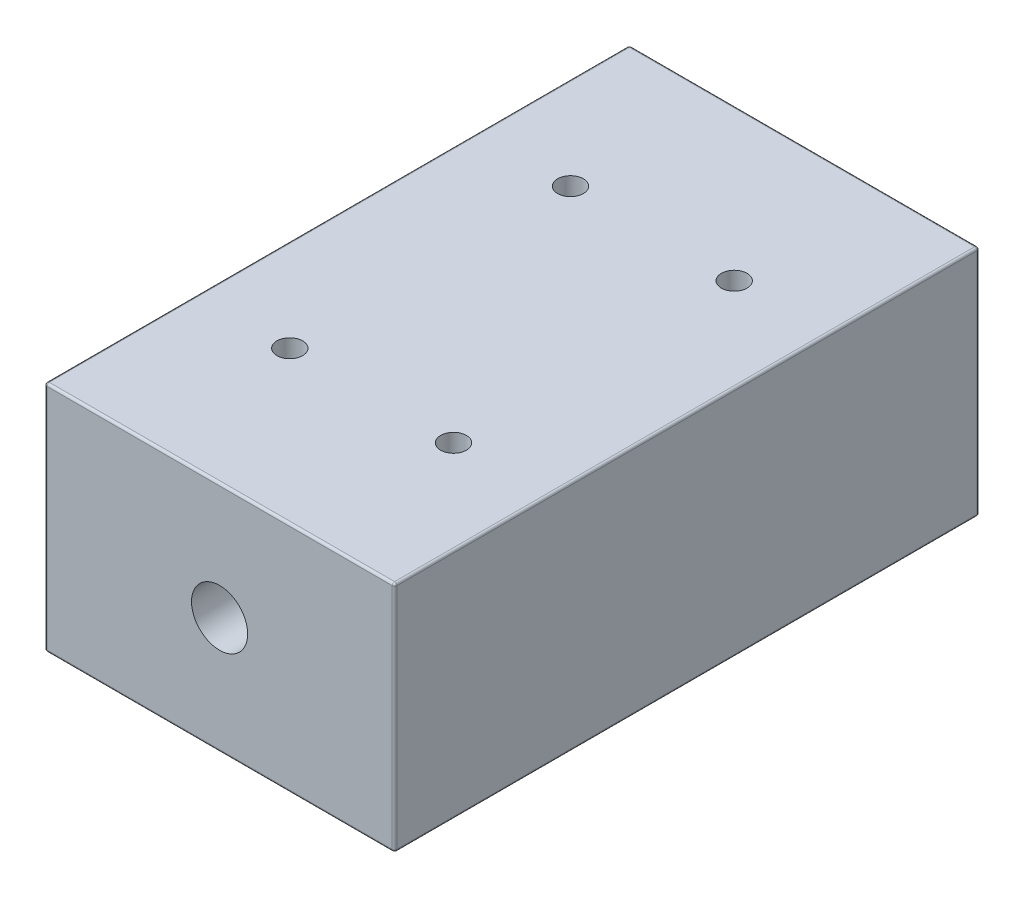
SolidWorks part; units mm, degrees
material "Beech"
ref_plane "Front Plane" through (0, 0, 0) normal (0, 0, 1) x (1, 0, 0)
ref_plane "Top Plane" through (0, 0, 0) normal (0, 1, 0) x (1, 0, 0)
ref_plane "Right Plane" through (0, 0, 0) normal (1, 0, 0) x (0, 0, -1)
sketch "Sketch1" plane through (0, 0, 0) normal (0, 0, 1) x (1, 0, 0)
  line L1 (0, 0) -> (74.8, 0)
  line L2 (0, 0) -> (0, 49.8)
  line L3 (0, 49.8) -> (74.8, 49.8)
  line L4 (74.8, 0) -> (74.8, 49.8)
  dimension "D1" = 74.8
  dimension "D2" = 49.8
extrude "slider body" add sketch "Sketch1" along normal blind 125
sketch "Sketch2" plane through (0, 0, 0) normal (0, 0, -1) x (-1, 0, 0)
  line L0 (-74.8, 49.8) -> (0, 0) construction
  line L1 (-74.8, 0) -> (0, 49.8) construction
  circle A0 centre (-37.4, 24.9) radius 11
  dimension "D1" = 22
extrude "lead nut inset" cut sketch "Sketch2" against normal blind 15
sketch "Sketch3" plane through (0, 0, 15) normal (0, 0, -1) x (-1, 0, 0)
  circle A0 centre (-37.4, 24.9) radius 6
  circle A1 centre (-37.4, 24.9) radius 11 construction
  dimension "D1" = 12
extrude "leadscrew clearance" cut sketch "Sketch3" against normal through all
fillet "corner break" radius 0.5 12 edges at (0, 24.9, 125) (0, 24.9, 0) (0, 0, 62.5) (37.4, 0, 125) (37.4, 0, 0) (74.8, 0, 62.5) (74.8, 24.9, 125) (74.8, 24.9, 0) (74.8, 49.8, 62.5) (37.4, 49.8, 125) (0, 49.8, 62.5) (37.4, 49.8, 0)
hole_wizard "bolt clearance holes" positions "Sketch4" profile "Sketch6" hole size "M5" standard "ANSI Metric" end condition through all
sketch "Sketch4" plane through (0, 49.8, 0) normal (0, 1, 0) x (1, 0, 0)
  line L1 (54.9, -92.5) -> (19.9, -92.5)
  line L2 (54.9, -92.5) -> (54.9, -32.5)
  line L3 (54.9, -32.5) -> (19.9, -32.5)
  line L4 (19.9, -92.5) -> (19.9, -32.5)
  line L5 (37.4, -92.5) -> (37.4, -124.5)
  line L6 (0.5, -124.5) -> (74.3, -124.5) construction
  line L8 (19.9, -62.5) -> (0.5, -62.5)
  line L9 (0.5, -0.5) -> (0.5, -124.5) construction
  point P1 (54.9, -92.5)
  point P2 (19.9, -32.5)
  point P47 (54.9, -32.5)
  point P48 (19.9, -92.5)
  dimension "D1" = 35
  dimension "D2" = 60
sketch "Sketch6" plane through (54.9, 49.8, 92.5) normal (1, 0, 0) x (0, 0, 1)
  line L0 (0, 0) -> (0, 49.8)
  line L1 (0, 49.8) -> (2.75, 49.8)
  line L2 (2.75, 49.8) -> (2.75, 0)
  line L5 (2.75, 0) -> (0, 0)
  line L11 (0, -6.35) -> (0, 107.95) construction
  dimension "Thru Hole Dia." = 5.5
  dimension "Thru Hole Depth" = 49.8
sketch "Sketch7" plane through (0, 0, 0) normal (0, -1, 0) x (1, 0, 0)
  circle A0 centre (19.9, 92.5) radius 6
  circle A1 centre (54.9, 92.5) radius 6
  circle A2 centre (54.9, 32.5) radius 6
  circle A3 centre (19.9, 32.5) radius 6
  dimension "D1" = 12
extrude "nut clearance counterbores" cut sketch "Sketch7" against normal blind 10
equation "\"board_thickness\" = 12mm"
equation "\"way_width\"= 75mm"
equation "\"way_thickness\"= 50mm"
equation "\"radial_clearance\"= 0.1mm"
equation "\"slider_width\"= \"way_width\"-2* \"radial_clearance\""
equation "\"slider_thickness\" = \"way_thickness\" - 2 * \"radial_clearance\""
equation "\"column_width\"= \"way_width\" + 2 * \"board_thickness\""
equation "\"boxway_slot_width\" = 50mm"
equation "\"keeper_rail_width\" = (\"column_width\" - \"boxway_slot_width\")/2"
equation "\"slider_length\" = 125mm"
equation "\"D1@Sketch1\"=\"slider_width\""
equation "\"D2@Sketch1\"=\"slider_thickness\""
equation "\"D1@slider body\" = \"slider_length\""
equation "\"nut_diameter\"= 22mm"
equation "\"nut_length\"= 15mm"
equation "\"D1@Sketch2\"=\"nut_diameter\""
equation "\"D1@lead nut inset\" = \"nut_length\""
equation "\"leadscrew_diameter\"= 10mm"
equation "\"leadscrew_radial_clearance\"= 1mm"
equation "\"D1@Sketch3\"=\"leadscrew_diameter\"+2* \"leadscrew_radial_clearance\""
equation "\"bearing_bolt_pattern_width\" = 35mm"
equation "\"bearing_bolt_pattern_height\" = 60mm"
equation "\"desktop_bolt_pattern_width\" = 30mm"
equation "\"desktop_bolt_pattern_height\" = 30mm"
equation "\"D1@Sketch4\"=\"bearing_bolt_pattern_width\""
equation "\"D2@Sketch4\"=\"bearing_bolt_pattern_height\""
equation "\"bearing_bolt_nut_counterbore_diameter\" = 12mm"
equation "\"bearing_bolt_nut_counterbore_depth\"= 10mm"
equation "\"D1@Sketch7\"=\"bearing_bolt_nut_counterbore_diameter\""
equation "\"D1@nut clearance counterbores\" = \"bearing_bolt_nut_counterbore_depth\""
